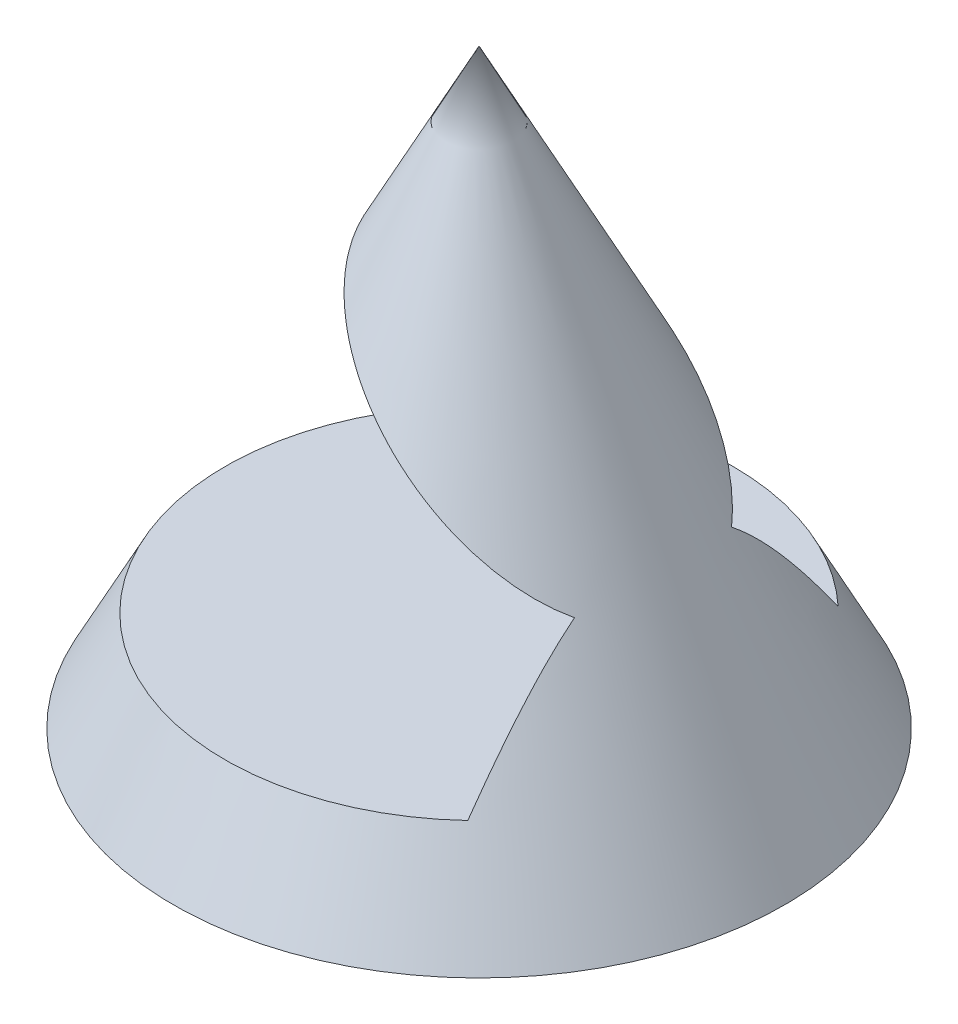
SolidWorks part; units mm, degrees
ref_plane "前视基准面" through (0, 0, 0) normal (0, 0, 1) x (1, 0, 0)
ref_plane "上视基准面" through (0, 0, 0) normal (0, 1, 0) x (1, 0, 0)
ref_plane "右视基准面" through (0, 0, 0) normal (1, 0, 0) x (0, 0, -1)
sketch "草图1" plane through (0, 0, 0) normal (0, 0, 1) x (1, 0, 0)
  line L0 (0, 0) -> (0, 29)
  line L1 (0, 29) -> (15, 0)
  line L2 (15, 0) -> (0, 0)
  dimension "D1" = 29
  dimension "D2" = 15
revolve "旋转1" add sketch "草图1" angle 360 about L0
sketch "草图2" plane through (0, 0, 0) normal (0, 0, 1) x (1, 0, 0)
  line L0 (-4.1379, 21) -> (8.5335, 10.8981)
  line L1 (-4.1379, 21) -> (-12.4665, 4.8981)
  line L3 (0, 29) -> (-15, 0) construction
  line L4 (8.5335, 10.8981) -> (8.5335, 4.8981)
  line L5 (8.5335, 4.8981) -> (-12.4665, 4.8981)
  dimension "D2" = 6
  dimension "D3" = 21
  dimension "D4" = 8
extrude "切除-拉伸1" cut sketch "草图2" against normal through all both and the other way through all contours L5 L4 L0 L1
